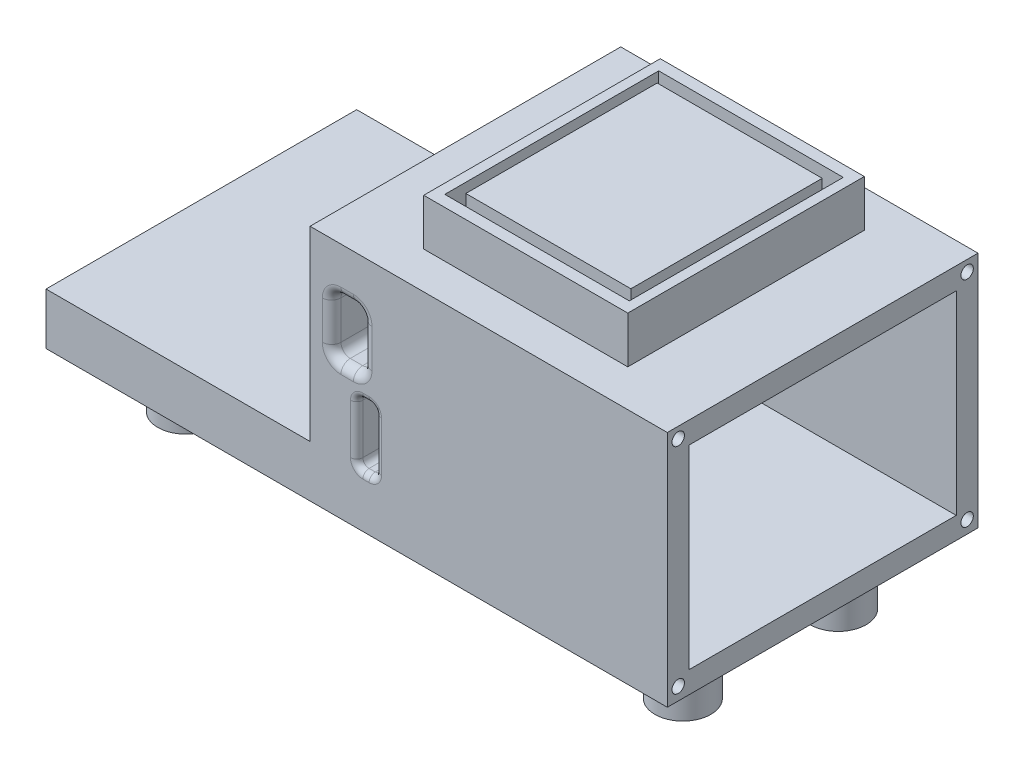
SolidWorks part; units mm, degrees
ref_plane "Front Plane" through (0, 0, 0) normal (0, 0, 1) x (1, 0, 0)
ref_plane "Top Plane" through (0, 0, 0) normal (0, 1, 0) x (1, 0, 0)
ref_plane "Right Plane" through (0, 0, 0) normal (1, 0, 0) x (0, 0, -1)
sketch "Sketch1" plane through (0, 0, 0) normal (0, 1, 0) x (1, 0, 0)
  line L7 (57.5, -50) -> (-57.5, -50)
  line L8 (57.5, -50) -> (57.5, 50)
  line L9 (57.5, 50) -> (-57.5, 50)
  line L10 (-57.5, -50) -> (-57.5, 50)
  line L11 (57.5, -50) -> (-57.5, 50) construction
  line L12 (57.5, 50) -> (-57.5, -50) construction
  point P0 (0, 0)
  dimension "D1" = 115
  dimension "D2" = 100
extrude "Boss-Extrude1" add sketch "Sketch1" along normal blind 40
sketch "Sketch8" plane through (0, 0, 0) normal (0, -1, 0) x (1, 0, 0)
  line L0 (57.5, -50) -> (-57.5, 50) construction
  line L1 (57.5, 50) -> (-57.5, -50) construction
  line L2 (57.5, 0) -> (-57.5, 0) construction
  line L3 (57.5, 50) -> (57.5, -50) construction
  line L4 (-57.5, -50) -> (-57.5, 50) construction
  line L5 (0, -50) -> (0, 50) construction
  line L6 (57.5, -50) -> (-57.5, -50) construction
  line L7 (-57.5, 50) -> (57.5, 50) construction
  circle A0 centre (0, 0) radius 7
  circle A1 centre (42.4079, -36.8764) radius 6
  circle A2 centre (42.4079, 36.8764) radius 6
  dimension "D1" = 12
  dimension "D3" = 14
  dimension "D2" = 20
extrude "Boss-Extrude4" add sketch "Sketch8" along normal blind 20
sketch "Sketch9" plane through (0, -20, 0) normal (0, -1, 0) x (1, 0, 0)
  line L0 (-57.5, 50) -> (57.5, 50) construction
  line L1 (57.5, -50) -> (-142.5, -50)
  line L2 (57.5, -50) -> (57.5, 50)
  line L3 (57.5, 50) -> (-142.5, 50)
  line L4 (-142.5, -50) -> (-142.5, 50)
  line L5 (57.5, -50) -> (-142.5, 50) construction
  line L6 (57.5, 50) -> (-142.5, -50) construction
  line L7 (57.5, 50) -> (57.5, -50) construction
  line L8 (57.5, -50) -> (-57.5, -50) construction
  point P4 (-42.5, 0)
  dimension "D1" = 200
extrude "Boss-Extrude5" add sketch "Sketch9" along normal blind 16.6
sketch "Sketch10" plane through (0, -36.6, 0) normal (0, -1, 0) x (1, 0, 0)
  line L0 (-42.5, -50) -> (-42.5, 50) construction
  line L1 (-142.5, -50) -> (57.5, -50) construction
  line L2 (57.5, 50) -> (-142.5, 50) construction
  line L3 (57.5, 0) -> (-142.5, 0) construction
  line L4 (57.5, -50) -> (57.5, 50) construction
  line L5 (-142.5, 50) -> (-142.5, -50) construction
  circle A0 centre (37.5, -25) radius 9
  circle A1 centre (-122.5, -25) radius 9
  circle A2 centre (-122.5, 25) radius 9
  circle A3 centre (37.5, 25) radius 9
  circle A4 centre (-42.5, 0) radius 10
  dimension "D1" = 18
  dimension "D4" = 20
  dimension "D2" = 20
  dimension "D3" = 25
  dimension "D5" = 20
extrude "Boss-Extrude7" add sketch "Sketch10" along normal blind 20
sketch "Sketch17" plane through (0, 0, 0) normal (0, -1, 0) x (1, 0, 0)
  line L0 (57.5, -50) -> (-57.5, -50) construction
  line L1 (-57.5, 50) -> (-42.5, 50)
  line L2 (-57.5, 50) -> (-57.5, -50)
  line L3 (-57.5, -50) -> (-42.5, -50)
  line L4 (-42.5, 50) -> (-42.5, -50)
  line L5 (-57.5, 50) -> (-42.5, -50) construction
  line L6 (-57.5, -50) -> (-42.5, 50) construction
  point P4 (-50, 0)
  dimension "D1" = 15
extrude "Boss-Extrude15" add sketch "Sketch17" along normal blind 20
sketch "Sketch15" plane through (0, -20, 0) normal (0, 1, 0) x (1, 0, 0)
  line L0 (-64.5, 0) -> (-57.5, 0) construction
  line L1 (-142.5, 50) -> (-57.5, 50) construction
  circle A0 centre (-78.6, 0) radius 14.1
  dimension "D1" = 28.2
  dimension "D2" = 50
  dimension "D3" = 7
extrude "Cut-Extrude2" cut sketch "Sketch15" against normal blind 10
sketch "Sketch21" plane through (0, -30, 0) normal (0, 1, 0) x (1, 0, 0)
  circle A0 centre (-85.1607, 0) radius 1.7674
  circle A1 centre (-73.2221, 0) radius 2.0384
extrude "Cut-Extrude3" cut sketch "Sketch21" against normal blind 20 contours A0 | A1
sketch "Sketch19" plane through (-57.5, 0, 0) normal (-1, 0, 0) x (0, 0, 1)
  line L0 (0, 40) -> (0, -20) construction
  line L1 (-50, 40) -> (50, 40) construction
  line L2 (50, -20) -> (-50, -20) construction
  line L3 (0, -13.4091) -> (-33.74, -13.4091) construction
  circle A0 centre (-32.14, -13.4091) radius 1.6
  circle A1 centre (32.14, -13.4091) radius 1.6
  circle A2 centre (-32.14, 14.6909) radius 1.6
  circle A3 centre (32.14, 14.6909) radius 1.6
  dimension "D2" = 3.2
  dimension "D4" = 3.2
  dimension "D1" = 33.74
  dimension "D3" = 28.1
extrude "Cut-Extrude4" cut sketch "Sketch19" against normal blind 23
sketch "Sketch22" plane through (-42.5, 0, 0) normal (1, 0, 0) x (0, 0, -1)
  line L0 (0, 0) -> (0, -20) construction
  line L1 (-28.3872, -13.4091) -> (-30.2636, -10.1591)
  line L2 (-30.2636, -10.1591) -> (-34.0164, -10.1591)
  line L3 (-34.0164, -10.1591) -> (-35.8928, -13.4091)
  line L4 (-35.8928, -13.4091) -> (-34.0164, -16.6591)
  line L5 (-34.0164, -16.6591) -> (-30.2636, -16.6591)
  line L6 (-30.2636, -16.6591) -> (-28.3872, -13.4091)
  line L7 (50, 0) -> (-50, 0) construction
  line L8 (50, -20) -> (-50, -20) construction
  line L9 (30.2636, -16.6591) -> (28.3872, -13.4091)
  line L10 (34.0164, -16.6591) -> (30.2636, -16.6591)
  line L11 (35.8928, -13.4091) -> (34.0164, -16.6591)
  line L12 (34.0164, -10.1591) -> (35.8928, -13.4091)
  line L13 (30.2636, -10.1591) -> (34.0164, -10.1591)
  line L14 (28.3872, -13.4091) -> (30.2636, -10.1591)
  circle A0 centre (-32.14, -13.4091) radius 3.25 construction
  dimension "D1" = 6.5
extrude "Cut-Extrude5" cut sketch "Sketch22" against normal blind 3
sketch "Sketch11" plane through (0, 40, 0) normal (0, 1, 0) x (1, 0, 0)
  line L0 (-57.5, 0) -> (57.5, 0) construction
  line L5 (-32.84, -38.07) -> (32.84, -38.07)
  line L6 (-32.84, -38.07) -> (-32.84, 38.07)
  line L11 (-32.84, 38.07) -> (32.84, 38.07)
  line L12 (32.84, -38.07) -> (32.84, 38.07)
  line L17 (-32.84, -38.07) -> (32.84, 38.07) construction
  line L18 (-32.84, 38.07) -> (32.84, -38.07) construction
  line L19 (-57.5, -50) -> (-57.5, 50) construction
  line L20 (57.5, -50) -> (57.5, 50) construction
  line L23 (-29.7, -34.4299) -> (29.7, -34.4299)
  line L24 (-29.7, -34.4299) -> (-29.7, 34.4299)
  line L25 (-29.7, 34.4299) -> (29.7, 34.4299)
  line L26 (29.7, -34.4299) -> (29.7, 34.4299)
  line L27 (-29.7, -34.4299) -> (29.7, 34.4299) construction
  line L28 (-29.7, 34.4299) -> (29.7, -34.4299) construction
  line L30 (-26.56, -30.7899) -> (26.56, -30.7899)
  line L31 (-26.56, -30.7899) -> (-26.56, 30.7899)
  line L32 (-26.56, 30.7899) -> (26.56, 30.7899)
  line L33 (26.56, -30.7899) -> (26.56, 30.7899)
  line L34 (-26.56, -30.7899) -> (26.56, 30.7899) construction
  line L35 (-26.56, 30.7899) -> (26.56, -30.7899) construction
  line L40 (-23.7511, -27.5337) -> (23.7511, 27.5337) construction
  line L41 (-23.6679, 27.6053) -> (23.6679, -27.6053) construction
  point P0 (0, 0)
  point P6 (0, 0)
  point P7 (0, 0)
  point P11 (0, 0)
  point P15 (0, 0)
  point P16 (0, 0)
  point P21 (0, 0)
  point P26 (0, 0)
  dimension "D1" = 65.68
  dimension "D2" = 76.14
  dimension "D3" = 3.14
  dimension "D4" = 3.14
  dimension "D5" = 59.4
  dimension "D6" = 68.8599
sketch "Sketch28" plane through (0, 0, 0) normal (0, -1, 0) x (1, 0, 0)
  line L0 (-42.5, 50) -> (57.5, 50) construction
  line L1 (-36.5, 50) -> (57.5, 50)
  line L2 (-36.5, 50) -> (-36.5, -50)
  line L3 (-36.5, -50) -> (57.5, -50)
  line L4 (57.5, 50) -> (57.5, -50)
  line L5 (-36.5, 50) -> (57.5, -50) construction
  line L6 (-36.5, -50) -> (57.5, 50) construction
  line L7 (-42.5, -50) -> (-42.5, 50) construction
  point P4 (10.5, 0)
  dimension "D1" = 6
extrude "Boss-Extrude16" add sketch "Sketch28" along normal blind 20
extrude "Boss-Extrude17" add sketch "Sketch11" along normal blind 15 contours L30 L33 L32 L31 | L5 L12 L11 L6 L26 L23 L24 L25
sketch "Sketch30" plane through (57.5, 0, 0) normal (1, 0, 0) x (0, 0, -1)
  line L0 (-50, 40) -> (50, 40) construction
  line L1 (-43, 33) -> (43, 33)
  line L2 (-43, 33) -> (-43, -29.6)
  line L3 (-43, -29.6) -> (43, -29.6)
  line L4 (43, 33) -> (43, -29.6)
  line L5 (-43, 33) -> (43, -29.6) construction
  line L6 (-43, -29.6) -> (43, 33) construction
  line L7 (-50, 40) -> (-50, -36.6) construction
  line L8 (50, 40) -> (50, -36.6) construction
  line L9 (50, -36.6) -> (-50, -36.6) construction
  point P4 (0, 1.7)
  dimension "D1" = 7
  dimension "D2" = 7
  dimension "D3" = 7
  dimension "D4" = 7
extrude "Cut-Extrude10" cut sketch "Sketch30" against normal blind 89
sketch "Sketch35" plane through (0, 40, 0) normal (0, 1, 0) x (1, 0, 0)
  line L0 (-29.7, -34.4299) -> (-29.7, 34.4299) construction
  line L1 (-29.7, -22.4299) -> (-26.7, -22.4299)
  line L2 (-29.7, -22.4299) -> (-29.7, -7.4299)
  line L3 (-29.7, -7.4299) -> (-26.7, -7.4299)
  line L4 (-26.7, -22.4299) -> (-26.7, -7.4299)
  line L5 (-29.7, -22.4299) -> (-26.7, -7.4299) construction
  line L6 (-29.7, -7.4299) -> (-26.7, -22.4299) construction
  line L7 (-29.7, -34.4299) -> (29.7, -34.4299) construction
  line L8 (-29.7, 34.4299) -> (29.7, 34.4299) construction
  line L9 (-29.7, 7.6099) -> (-26.7, 7.6099)
  line L10 (-29.7, 7.6099) -> (-29.7, 22.6099)
  line L11 (-29.7, 22.6099) -> (-26.7, 22.6099)
  line L12 (-26.7, 7.6099) -> (-26.7, 22.6099)
  line L13 (-29.7, 7.6099) -> (-26.7, 22.6099) construction
  line L14 (-29.7, 22.6099) -> (-26.7, 7.6099) construction
  line L15 (0, -50) -> (0, 50) construction
  line L16 (-57.5, -50) -> (57.5, -50) construction
  line L17 (57.5, 50) -> (-57.5, 50) construction
  line L18 (29.7, 22.6099) -> (26.7, 22.6099)
  line L19 (26.7, 7.6099) -> (26.7, 22.6099)
  line L20 (29.7, 7.6099) -> (26.7, 7.6099)
  line L21 (29.7, 7.6099) -> (29.7, 22.6099)
  line L22 (29.7, -7.4299) -> (26.7, -7.4299)
  line L23 (26.7, -22.4299) -> (26.7, -7.4299)
  line L24 (29.7, -22.4299) -> (26.7, -22.4299)
  line L25 (29.7, -22.4299) -> (29.7, -7.4299)
  line L26 (29.7, -34.4299) -> (29.7, 34.4299) construction
  line L27 (-22.7, -34.1399) -> (-7.7, -34.1399)
  line L28 (-22.7, -34.1399) -> (-22.7, -31.1399)
  line L29 (-22.7, -31.1399) -> (-7.7, -31.1399)
  line L30 (-7.7, -34.1399) -> (-7.7, -31.1399)
  line L31 (-22.7, -34.1399) -> (-7.7, -31.1399) construction
  line L32 (-22.7, -31.1399) -> (-7.7, -34.1399) construction
  line L34 (-26.56, -30.7899) -> (26.56, -30.7899) construction
  line L36 (7.7, -34.1399) -> (22.7, -34.1399)
  line L37 (7.7, -34.1399) -> (7.7, -31.1399)
  line L38 (7.7, -31.1399) -> (22.7, -31.1399)
  line L39 (22.7, -34.1399) -> (22.7, -31.1399)
  line L40 (7.7, -34.1399) -> (22.7, -31.1399) construction
  line L41 (7.7, -31.1399) -> (22.7, -34.1399) construction
  line L42 (-32.84, 0) -> (32.84, 0) construction
  line L43 (-32.84, -38.07) -> (-32.84, 38.07) construction
  line L44 (32.84, -38.07) -> (32.84, 38.07) construction
  line L45 (7.7, 31.1399) -> (22.7, 31.1399)
  line L46 (22.7, 34.1399) -> (22.7, 31.1399)
  line L47 (7.7, 34.1399) -> (22.7, 34.1399)
  line L48 (7.7, 34.1399) -> (7.7, 31.1399)
  line L49 (-22.7, 31.1399) -> (-7.7, 31.1399)
  line L50 (-7.7, 34.1399) -> (-7.7, 31.1399)
  line L51 (-22.7, 34.1399) -> (-7.7, 34.1399)
  line L52 (-22.7, 34.1399) -> (-22.7, 31.1399)
  point P4 (-28.2, -14.9299)
  point P13 (-28.2, 15.1099)
  point P34 (-15.2, -32.6399)
  point P41 (15.2, -32.6399)
  dimension "D1" = 15
  dimension "D2" = 3
  dimension "D3" = 12
  dimension "D4" = 15
  dimension "D5" = 3
  dimension "D6" = 11.82
  dimension "D7" = 15
  dimension "D8" = 3
  dimension "D9" = 0.35
  dimension "D10" = 0.2901
  dimension "D11" = 7
  dimension "D12" = 15
  dimension "D13" = 3
  dimension "D14" = 0.35
  dimension "D15" = 15.4
  dimension "D16" = 7
extrude "Cut-Extrude14" cut sketch "Sketch35" against normal blind 3
sketch "Sketch36" plane through (0, 0, 50) normal (0, 0, 1) x (1, 0, 0)
  line L0 (-57.5, 40) -> (57.5, 40) construction
  line L1 (-50.5615, 25) -> (-40.5615, 25)
  line L2 (-50.5615, 25) -> (-50.5615, 6.6251)
  line L3 (-50.5615, 6.6251) -> (-40.5615, 6.6251)
  line L4 (-40.5615, 25) -> (-40.5615, 6.6251)
  line L5 (-50.5615, 25) -> (-40.5615, 6.6251) construction
  line L6 (-50.5615, 6.6251) -> (-40.5615, 25) construction
  point P4 (-45.5615, 15.8126)
  dimension "D1" = 10
  dimension "D2" = 18.3749
  dimension "D3" = 15
extrude "Cut-Extrude15" cut sketch "Sketch36" against normal blind 168
sketch "Sketch38" plane through (-42.5, 0, 0) normal (1, 0, 0) x (0, 0, -1)
  line L5 (0, 0) -> (0, -20) construction
  line L6 (50, 0) -> (-50, 0) construction
  line L8 (50, -20) -> (-50, -20) construction
  line L10 (-21.5579, 0) -> (21.5579, 0)
  line L11 (-21.5579, 0) -> (-21.5579, -20)
  line L12 (-21.5579, -20) -> (21.5579, -20)
  line L13 (21.5579, 0) -> (21.5579, -20)
  line L14 (-21.5579, 0) -> (21.5579, -20) construction
  line L15 (-21.5579, -20) -> (21.5579, 0) construction
  point P10 (0, -10)
extrude "Boss-Extrude18" add sketch "Sketch38" along normal blind 10
sketch "Sketch39" plane through (-50.5615, 0, 0) normal (1, 0, 0) x (0, 0, -1)
  line L0 (0, 25) -> (0, 6.6251) construction
  line L1 (50, 25) -> (-50, 25) construction
  line L2 (50, 6.6251) -> (-50, 6.6251) construction
  line L4 (-18, 25) -> (18, 25)
  line L5 (-18, 25) -> (-18, 6.6251)
  line L6 (-18, 6.6251) -> (18, 6.6251)
  line L7 (18, 25) -> (18, 6.6251)
  line L8 (-18, 25) -> (18, 6.6251) construction
  line L9 (-18, 6.6251) -> (18, 25) construction
  point P10 (0, 15.8126)
  dimension "D1" = 36
extrude "Boss-Extrude19" add sketch "Sketch39" along normal blind 10
sketch "Sketch40" plane through (-50.5615, 0, 0) normal (1, 0, 0) x (0, 0, -1)
  line L0 (50, 6.6251) -> (18, 6.6251) construction
  line L1 (34.0164, 17.9409) -> (30.2636, 17.9409)
  line L2 (30.2636, 17.9409) -> (28.3872, 14.6909)
  line L3 (28.3872, 14.6909) -> (30.2636, 11.4409)
  line L4 (30.2636, 11.4409) -> (34.0164, 11.4409)
  line L5 (34.0164, 11.4409) -> (35.8928, 14.6909)
  line L6 (35.8928, 14.6909) -> (34.0164, 17.9409)
  line L7 (-30.2636, 17.9409) -> (-34.0164, 17.9409)
  line L8 (-34.0164, 17.9409) -> (-35.8928, 14.6909)
  line L9 (-35.8928, 14.6909) -> (-34.0164, 11.4409)
  line L10 (-34.0164, 11.4409) -> (-30.2636, 11.4409)
  line L11 (-30.2636, 11.4409) -> (-28.3872, 14.6909)
  line L12 (-28.3872, 14.6909) -> (-30.2636, 17.9409)
  line L13 (-18, 6.6251) -> (-50, 6.6251) construction
  circle A0 centre (32.14, 14.6909) radius 3.25 construction
  circle A1 centre (-32.14, 14.6909) radius 3.25 construction
  dimension "D1" = 6.5
  dimension "D2" = 6.5
extrude "Cut-Extrude16" cut sketch "Sketch40" against normal blind 3
fillet "Fillet1" radius 3 24 edges at (-50.5615, 15.8126, 50) (-45.5615, 6.6251, 50) (-40.5615, 15.8126, 50) (-45.5615, 6.6251, 18) (-40.5615, 15.8126, 18) (-40.5615, 6.6251, 34) (-50.5615, 6.6251, 34) (-50.5615, 15.8126, 18) (-45.5615, 25, 50) (-40.5615, 25, 34) (-45.5615, 25, 18) (-50.5615, 25, 34) (-40.5615, 6.6251, -34) (-40.5615, 15.8126, -50) (-40.5615, 25, -34) (-40.5615, 15.8126, -18) (-45.5615, 25, -18) (-50.5615, 15.8126, -18) (-45.5615, 6.6251, -18) (-50.5615, 6.6251, -34) (-45.5615, 6.6251, -50) (-45.5615, 25, -50) (-50.5615, 15.8126, -50) (-50.5615, 25, -34)
fillet "Fillet12" radius 2 12 edges at (-42.5, -10, -50) (-39.5, -20, -50) (-39.5, 0, -50) (-42.5, -20, -35.779) (-36.5, -10, -50) (-36.5, -20, -35.779) (-39.5, -20, -21.5579) (-42.5, -10, -21.5579) (-36.5, 0, -35.779) (-42.5, 0, -35.779) (-39.5, 0, -21.5579) (-36.5, -10, -21.5579)
fillet "Fillet13" radius 2 12 edges at (-36.5, -10, 50) (-39.5, -20, 50) (-39.5, 0, 50) (-42.5, -10, 50) (-42.5, -20, 35.779) (-36.5, -20, 35.779) (-36.5, 0, 35.779) (-42.5, 0, 35.779) (-39.5, -20, 21.5579) (-39.5, 0, 21.5579) (-36.5, -10, 21.5579) (-42.5, -10, 21.5579)
sketch "Sketch41" plane through (57.5, 0, 0) normal (1, 0, 0) x (0, 0, -1)
  line L0 (-50, 40) -> (-43, 33) construction
  line L1 (0, -36.6) -> (0, 40) construction
  line L2 (50, -36.6) -> (-50, -36.6) construction
  line L3 (-50, 40) -> (50, 40) construction
  line L4 (-50, 2) -> (50, 2) construction
  circle A0 centre (-46.5, 36.5) radius 2
  circle A1 centre (-46.5, -32.5) radius 2
  circle A2 centre (46.5, 36.5) radius 2
  circle A3 centre (46.5, -32.5) radius 2
  dimension "D1" = 4
extrude "Cut-Extrude17" cut sketch "Sketch41" against normal blind 10
